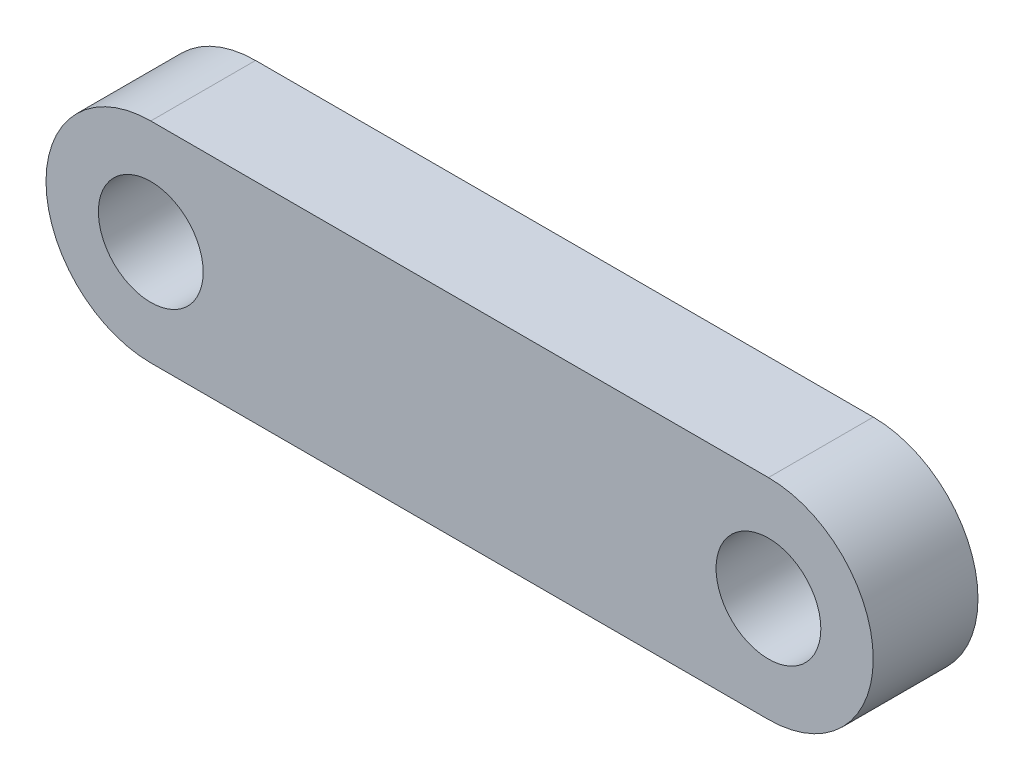
SolidWorks part; units mm, degrees
ref_plane "前基準面" through (0, 0, 0) normal (0, 0, 1) x (1, 0, 0)
ref_plane "上基準面" through (0, 0, 0) normal (0, 1, 0) x (1, 0, 0)
ref_plane "右基準面" through (0, 0, 0) normal (1, 0, 0) x (0, 0, -1)
sketch "草圖1" plane through (0, 0, 0) normal (0, 0, 1) x (1, 0, 0)
  line L0 (-5.895, 2.0003) -> (5.895, 2.0003)
  line L1 (-5.895, -1.9997) -> (5.895, -1.9997)
  arc A0 (-5.895, 2.0003) -> (-5.895, -1.9997) centre (-5.895, 0.0003) ccw
  arc A1 (5.895, -1.9997) -> (5.895, 2.0003) centre (5.895, 0.0003) ccw
  circle A2 centre (-5.895, 0.0003) radius 1
  circle A3 centre (5.895, 0.0003) radius 1
  dimension "D1" = 11.79
  dimension "D2" = 2
  dimension "D3" = 2
  dimension "D4" = 2
  dimension "D5" = 5.895
extrude "填料-伸長1" add sketch "草圖1" along normal blind 2
